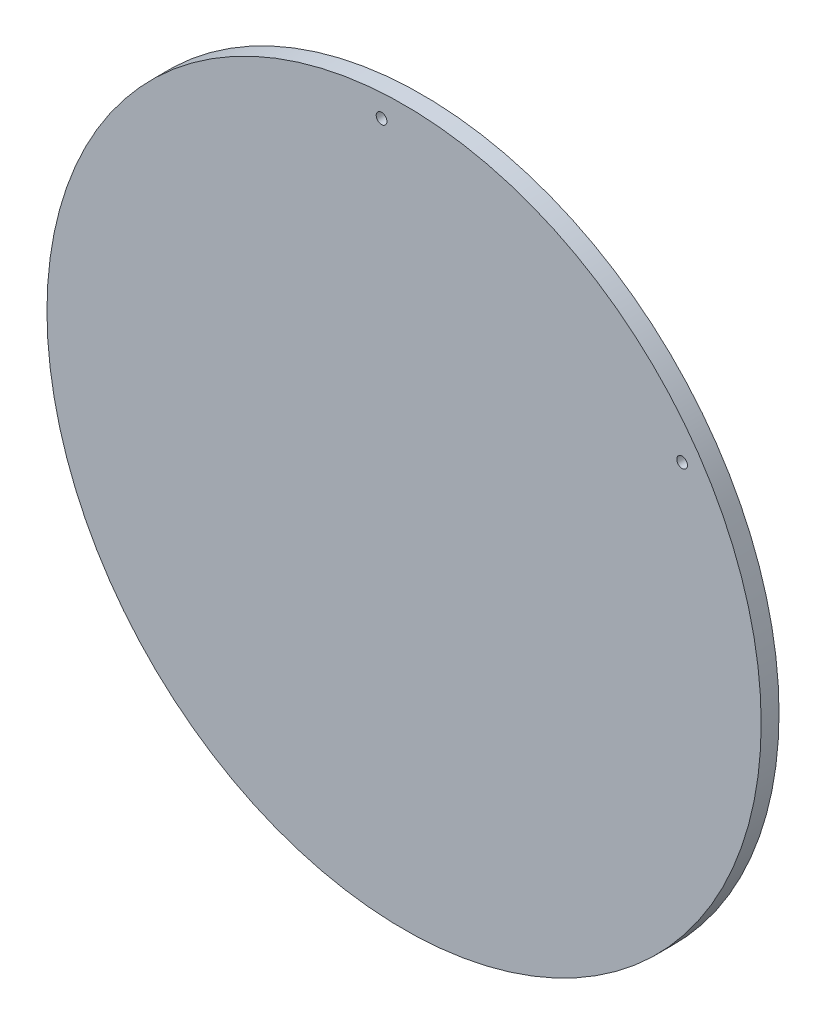
SolidWorks part; units mm, degrees
ref_plane "Front Plane" through (0, 0, 0) normal (0, 0, 1) x (1, 0, 0)
ref_plane "Top Plane" through (0, 0, 0) normal (0, 1, 0) x (1, 0, 0)
ref_plane "Right Plane" through (0, 0, 0) normal (1, 0, 0) x (0, 0, -1)
sketch "Sketch1" plane through (0, 0, 0) normal (0, 0, 1) x (1, 0, 0)
  circle A0 centre (0, 0) radius 200
  circle A1 centre (0, 0) radius 187.5 construction
  circle A2 centre (155.7063, 104.4595) radius 3
  circle A3 centre (168.3177, -82.6159) radius 3
  circle A4 centre (12.6114, -187.0754) radius 3
  circle A5 centre (-155.7063, -104.4595) radius 3
  circle A6 centre (-168.3177, 82.6159) radius 3
  circle A7 centre (-12.6114, 187.0754) radius 3
  point P7 (0, 0)
  point P8 (0, 0)
  point P18 (0, 0)
  dimension "D1" = 400
  dimension "D2" = 12.5
  dimension "D3" = 6
  dimension "D4" = 6
extrude "Boss-Extrude1" add sketch "Sketch1" along normal blind 10 contours A0 | A2 | A7
scale "Scale1" scale about centroid uniform scaling yes scale factor 10
